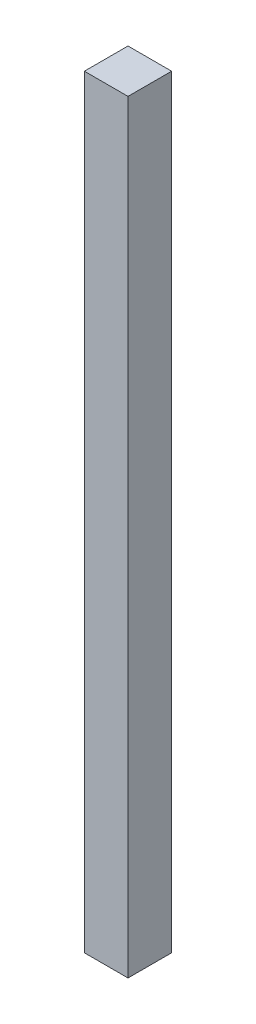
SolidWorks part; units mm, degrees
ref_plane "Front Plane" through (0, 0, 0) normal (0, 0, 1) x (1, 0, 0)
ref_plane "Top Plane" through (0, 0, 0) normal (0, 1, 0) x (1, 0, 0)
ref_plane "Right Plane" through (0, 0, 0) normal (1, 0, 0) x (0, 0, -1)
sketch "Sketch1" plane through (0, 0, 0) normal (0, 1, 0) x (1, 0, 0)
  line L1 (0, 0) -> (20, 0)
  line L2 (0, 0) -> (0, 20)
  line L3 (0, 20) -> (20, 20)
  line L4 (20, 0) -> (20, 20)
  dimension "D1" = 20
extrude "Boss-Extrude1" add sketch "Sketch1" along normal blind 350 contours L3 L4 L1 L2
